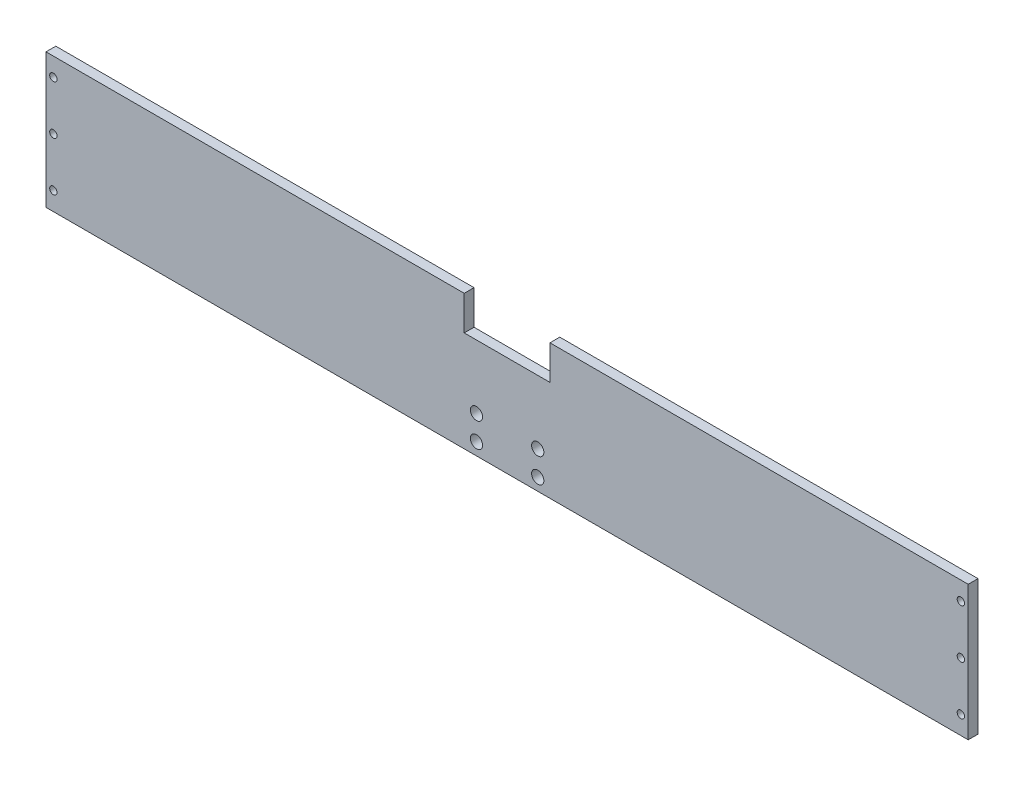
SolidWorks part; units mm, degrees
ref_plane "Plan de face" through (0, 0, 0) normal (0, 0, 1) x (1, 0, 0)
ref_plane "Plan de dessus" through (0, 0, 0) normal (0, 1, 0) x (1, 0, 0)
ref_plane "Plan de droite" through (0, 0, 0) normal (1, 0, 0) x (0, 0, -1)
sketch "Esquisse1" plane through (0, 0, 0) normal (0, 0, 1) x (1, 0, 0)
  line L1 (0, 0) -> (752.95, 0)
  line L2 (0, 0) -> (0, 110)
  line L3 (0, 110) -> (752.95, 110)
  line L4 (752.95, 0) -> (752.95, 110)
  dimension "D1" = 752.95
  dimension "D2" = 110
extrude "Boss.-Extru.1" add sketch "Esquisse1" along normal blind 8
sketch "Esquisse2" plane through (0, 0, 8) normal (0, 0, 1) x (1, 0, 0)
  line L0 (376.475, -42.2256) -> (376.475, 152.869) construction
  line L1 (0, 110) -> (0, 0) construction
  line L3 (0, 0) -> (752.95, 0) construction
  circle A0 centre (351.475, 30) radius 5
  circle A1 centre (351.475, 10) radius 5
  circle A2 centre (401.475, 30) radius 5
  circle A3 centre (401.475, 10) radius 5
  dimension "D2" = 10
  dimension "D3" = 10
  dimension "D4" = 10
  dimension "D5" = 20
  dimension "D6" = 25
  dimension "D7" = 25
  dimension "D1" = 376.475
extrude "Enlèv. mat.-Extru.1" cut sketch "Esquisse2" against normal up to next
sketch "Esquisse3" plane through (0, 0, 8) normal (0, 0, 1) x (1, 0, 0)
  line L0 (0, 0) -> (752.95, 0) construction
  line L1 (752.95, 110) -> (0, 110) construction
  line L2 (0, 110) -> (0, 0) construction
  line L3 (376.475, 110) -> (376.475, -54.7116) construction
  circle A0 centre (6, 95) radius 3
  circle A1 centre (6, 55) radius 3
  circle A2 centre (6, 15) radius 3
  circle A3 centre (746.95, 15) radius 3
  circle A4 centre (746.95, 55) radius 3
  circle A5 centre (746.95, 95) radius 3
  dimension "D1" = 6
  dimension "D2" = 6
  dimension "D3" = 6
  dimension "D4" = 15
  dimension "D5" = 15
  dimension "D6" = 55
  dimension "D7" = 6
  dimension "D8" = 6
  dimension "D9" = 6
extrude "Enlèv. mat.-Extru.2" cut sketch "Esquisse3" against normal up to next
sketch "Esquisse4" plane through (0, 0, 8) normal (0, 0, 1) x (1, 0, 0)
  line L0 (376.475, 110) -> (376.475, -22.4172) construction
  line L1 (752.95, 110) -> (0, 110) construction
  line L3 (341.475, 82) -> (411.475, 82)
  line L4 (341.475, 82) -> (341.475, 110)
  line L5 (341.475, 110) -> (411.475, 110)
  line L6 (411.475, 82) -> (411.475, 110)
  line L7 (341.475, 82) -> (411.475, 110) construction
  line L8 (341.475, 110) -> (411.475, 82) construction
  point P4 (376.475, 96)
  dimension "D1" = 28
  dimension "D2" = 70
extrude "Enlèv. mat.-Extru.3" cut sketch "Esquisse4" against normal up to next
